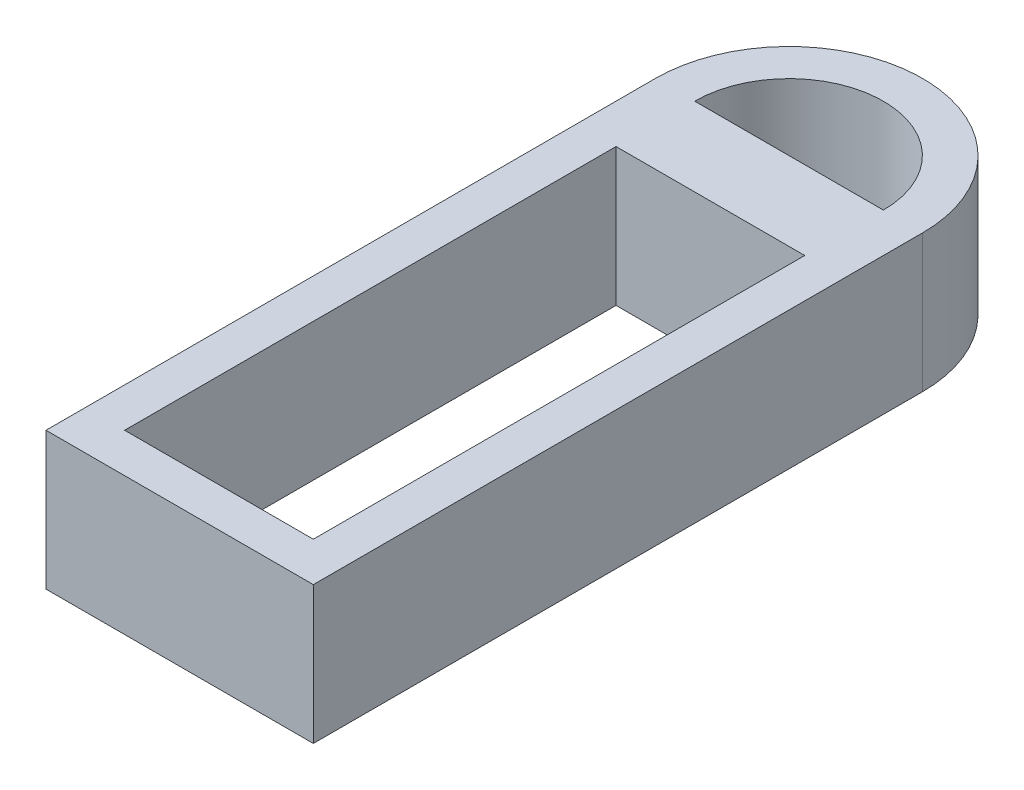
SolidWorks part; units mm, degrees
ref_plane "Front Plane" through (0, 0, 0) normal (0, 0, 1) x (1, 0, 0)
ref_plane "Top Plane" through (0, 0, 0) normal (0, 1, 0) x (1, 0, 0)
ref_plane "Right Plane" through (0, 0, 0) normal (1, 0, 0) x (0, 0, -1)
sketch "Sketch1" plane through (0, 0, 0) normal (0, 1, 0) x (1, 0, 0)
  line L0 (-3.4, 7.25) -> (3.4, 7.25)
  line L1 (-2.4, -6.25) -> (2.4, -6.25)
  line L2 (-2.4, -6.25) -> (-2.4, 6.25)
  line L3 (-2.4, 6.25) -> (2.4, 6.25)
  line L4 (2.4, -6.25) -> (2.4, 6.25)
  line L5 (-2.4, -6.25) -> (2.4, 6.25) construction
  line L6 (-2.4, 6.25) -> (2.4, -6.25) construction
  line L7 (3.4, -7.25) -> (3.4, 7.25)
  line L8 (-3.4, -7.25) -> (3.4, -7.25)
  line L9 (-3.4, -7.25) -> (-3.4, 7.25)
  point P0 (0, 0)
  dimension "D1" = 4.8
  dimension "D2" = 12.5
  dimension "D3" = 1
extrude "Boss-Extrude1" add sketch "Sketch1" along normal blind 3.5
sketch "Sketch2" plane through (0, 3.5, 0) normal (0, 1, 0) x (1, 0, 0)
  line L1 (-3.4, 7.25) -> (3.4, 7.25)
  line L2 (-3.4, 7.25) -> (-3.4, 8.25)
  line L3 (-2.4, 8.25) -> (2.4, 8.25)
  line L4 (3.4, 7.25) -> (3.4, 8.25)
  arc A0 (-3.4, 8.25) -> (3.4, 8.25) centre (0, 8.25) cw
  arc A1 (-2.4, 8.25) -> (2.4, 8.25) centre (0, 8.25) cw
  dimension "D1" = 1
  dimension "D2" = 1
extrude "Boss-Extrude2" add sketch "Sketch2" against normal blind 3.5
